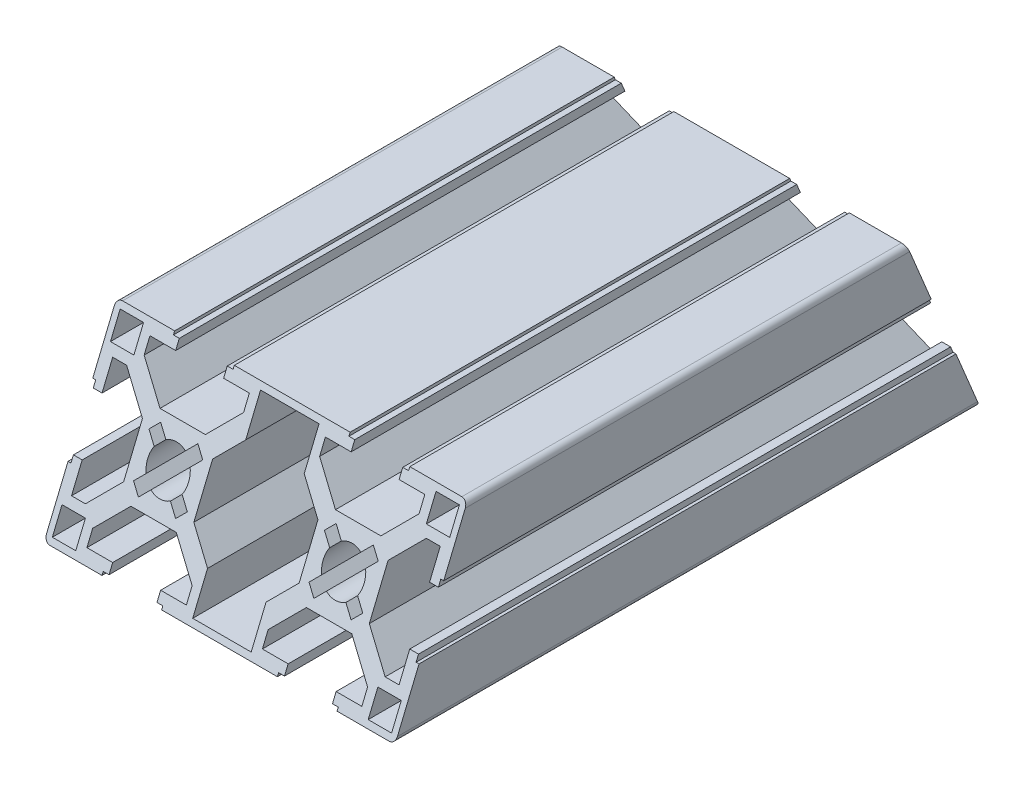
SolidWorks part; units mm, degrees
material "6063-T83"
ref_plane "Plano frontal" through (0, 0, 0) normal (0, 0, 1) x (1, 0, 0)
ref_plane "Plano superior" through (0, 0, 0) normal (0, 1, 0) x (1, 0, 0)
ref_plane "Plano direito" through (0, 0, 0) normal (1, 0, 0) x (0, 0, -1)
sketch "Esboço1" plane through (0, 0, 0) normal (0, 0, 1) x (1, 0, 0)
  line L5 (0, 0) -> (-17.7944, 17.7944) construction
  line L6 (0, 3.5) -> (0, 6)
  line L8 (0, 6) -> (-3.8787, 6)
  line L9 (-3.5, 0) -> (-6, 0)
  line L48 (-6, 0) -> (-6, 3.8787)
  line L49 (-3.8787, 6) -> (-8.5, 10.6213)
  line L50 (-6, 3.8787) -> (-10.6213, 8.5)
  line L51 (0, 0) -> (-12.921, 0) construction
  line L52 (-8.5, 13) -> (-4.1, 13)
  line L53 (-4.1, 13) -> (-4.1, 14.5)
  line L54 (-4.1, 14.5) -> (-5.1, 14.5)
  line L55 (-5.1, 14.5) -> (-5.1, 15)
  line L56 (-5.1, 15) -> (-15, 15)
  line L57 (-15, 5.1) -> (-15, 15)
  line L58 (-14.5, 5.1) -> (-15, 5.1)
  line L59 (-14.5, 4.1) -> (-14.5, 5.1)
  line L60 (-13, 4.1) -> (-14.5, 4.1)
  line L61 (-13, 8.5) -> (-13, 4.1)
  line L62 (-1.6646, 3.0788) -> (-3.182, 4.5962)
  line L63 (-3.0788, 1.6646) -> (-4.5962, 3.182)
  line L64 (-4.5962, 3.182) -> (-3.182, 4.5962)
  line L65 (-8.5, 13) -> (-8.5, 10.6213)
  line L66 (-10, 14) -> (-14, 14)
  line L67 (-10, 14) -> (-10, 10)
  line L68 (-10, 10) -> (-14, 10)
  line L69 (-14, 14) -> (-14, 10)
  line L70 (-10, 14) -> (-14, 10) construction
  line L71 (-10, 10) -> (-14, 14) construction
  line L72 (-13, 8.5) -> (-10.6213, 8.5)
  circle A1 centre (0, 0) radius 3.5
  point P25 (-12, 12)
  dimension "D5" = 10.9
  dimension "D9" = 5.5
  dimension "D10" = 2
  dimension "D11" = 4
  dimension "D12" = 4
  dimension "D13" = 1
  dimension "D1" = 7
  dimension "D2" = 6
  dimension "D3" = 3
  dimension "D4" = 9.9
  dimension "D6" = 0.5
  dimension "D7" = 1.5
  dimension "D8" = 15
  dimension "D14" = 6.5
extrude "Ressalto-extrusão1" add sketch "Esboço1" along normal blind 100 contours A1 L6 L8 L49 L65 L52 L53 L54 L55 L56 L57 L58 L59 L60 L61 L72 L50 L48 L9 L63 L64 L62 L69 L66 L67 L68
sketch "Esboço3" plane through (0, 0, 0) normal (1, 0, 0) x (0, 0, -1)
  line L0 (0, 0) -> (-1000, 0) construction
  dimension "D1" = 1000
pattern_circular "PadrãoCircular1" count 4 over 360 about axis through (0, 0, 0) along (0, 0, 1) of "Ressalto-extrusão1"
pattern_linear "Padrão linear1" count 2 spacing 30 along (1, 0, 0) of "Ressalto-extrusão1", "PadrãoCircular1"
sketch "Esboço4" plane through (0, 0, 0) normal (0, 0, -1) x (-1, 0, 0)
  line L0 (-20, 14) -> (-20, -14)
  line L1 (-20, -14) -> (-10, -14)
  line L2 (-10, -14) -> (-10, 14)
  line L3 (-10, 14) -> (-20, 14)
extrude "Corte-extrusão1" cut sketch "Esboço4" against normal through all
fillet "Filete1" radius 1 4 edges at (45, -15, 50) (45, 15, 50) (-15, 15, 50) (-15, -15, 50)
sketch "Sketch1" plane through (-15, 0, 0) normal (-1, 0, 0) x (0, 0, 1)
  line L0 (0, -15) -> (12.4264, 15)
  line L2 (12.4264, 15) -> (0, 15)
  line L3 (0, 15) -> (0, -15)
  line L4 (0, -5.1) -> (0, -14) construction
  line L5 (50, -14) -> (50, 14) construction
  line L6 (0, -14) -> (100, -14) construction
  line L7 (100, 14) -> (0, 14) construction
  line L8 (100, -15) -> (87.5736, 15)
  line L9 (100, 15) -> (100, -15)
  line L10 (87.5736, 15) -> (100, 15)
  point P2 (0, 0)
  dimension "D1" = 15
  dimension "D2" = 30
  dimension "D3" = 22.5
  dimension "D4" = 0
extrude "Cut-Extrude1" cut sketch "Sketch1" against normal through all
sketch "Sketch2" plane through (0, -15, 0) normal (0, -1, 0) x (1, 0, 0)
  line L0 (-14, 50) -> (44, 50)
  line L1 (-14, 100) -> (-14, 0) construction
  line L2 (44, 0) -> (44, 100) construction
